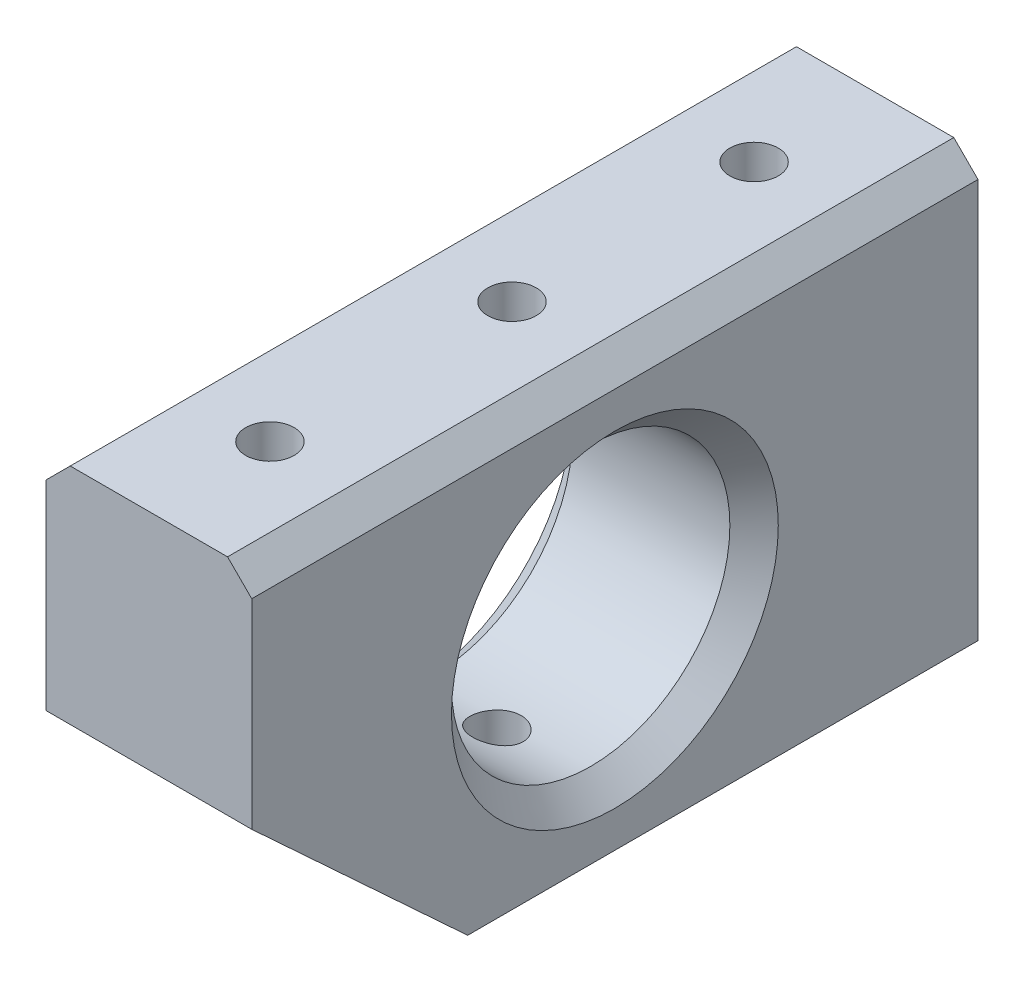
SolidWorks part; units mm, degrees
ref_plane "Front Plane" through (0, 0, 0) normal (0, 0, 1) x (1, 0, 0)
ref_plane "Top Plane" through (0, 0, 0) normal (0, 1, 0) x (1, 0, 0)
ref_plane "Right Plane" through (0, 0, 0) normal (1, 0, 0) x (0, 0, -1)
sketch "Sketch1" plane through (0, 0, 0) normal (0, 0, 1) x (1, 0, 0)
  line L1 (0, 0) -> (21.59, 0)
  line L2 (0, 0) -> (0, 46.99)
  line L3 (0, 46.99) -> (21.59, 46.99)
  line L4 (21.59, 0) -> (21.59, 46.99)
  dimension "D1" = 21.59
  dimension "D2" = 46.99
extrude "Boss-Extrude1" add sketch "Sketch1" along normal blind 76.2
sketch "Sketch2" plane through (21.59, 0, 0) normal (1, 0, 0) x (0, 0, -1)
  line L3 (-76.2, 46.99) -> (0, 46.99) construction
  line L4 (0, 0) -> (0, 46.99) construction
  circle A43 centre (-38.1, 23.495) radius 14.605
  dimension "D1" = 29.21
  dimension "D2" = 23.495
  dimension "1" = 38.1
extrude "Cut-Extrude1" cut sketch "Sketch2" against normal through all
sketch "Sketch3" plane through (21.59, 0, 0) normal (1, 0, 0) x (0, 0, -1)
  line L0 (-50.8, 0) -> (-76.2, 23.495)
  line L1 (-76.2, 0) -> (0, 0) construction
  line L2 (-76.2, 0) -> (-76.2, 46.99) construction
  line L3 (-76.2, 23.495) -> (-76.2, 0)
  line L4 (-76.2, 0) -> (-50.8, 0)
  dimension "D1" = 25.4
extrude "Cut-Extrude2" cut sketch "Sketch3" against normal through all
sketch "Sketch4" plane through (0, 46.99, 0) normal (0, 1, 0) x (1, 0, 0)
  line L0 (21.59, -76.2) -> (21.59, 0) construction
  line L1 (21.59, 0) -> (0, 0) construction
  circle A0 centre (10.795, -12.7) radius 2.54
  circle A1 centre (10.795, -38.1) radius 2.54
  circle A2 centre (10.795, -63.5) radius 2.54
  dimension "D1" = 5.08
  dimension "D2" = 10.795
  dimension "D3" = 12.7
  dimension "D4" = 25.4
  dimension "D5" = 25.4
extrude "Cut-Extrude3" cut sketch "Sketch4" against normal up to next
sketch "Sketch5" plane through (0, 0, 0) normal (0, -1, 0) x (1, 0, 0)
  line L0 (10.795, 50.8) -> (10.795, 0) construction
  line L1 (0, 50.8) -> (21.59, 50.8) construction
  line L2 (0, 0) -> (21.59, 0) construction
  circle A0 centre (10.795, 12.7) radius 2.54
  circle A1 centre (10.795, 39.6875) radius 2.54
  dimension "D3" = 5.08
  dimension "D1" = 12.7
  dimension "D2" = 26.9875
extrude "Cut-Extrude4" cut sketch "Sketch5" against normal up to next
chamfer "Chamfer1" distance 2.54 angle 45 6 edges at (0, 23.495, 23.495) (21.59, 23.495, 23.495) (0, 46.99, 38.1) (0, 0, 25.4) (21.59, 46.99, 38.1) (21.59, 0, 25.4)
